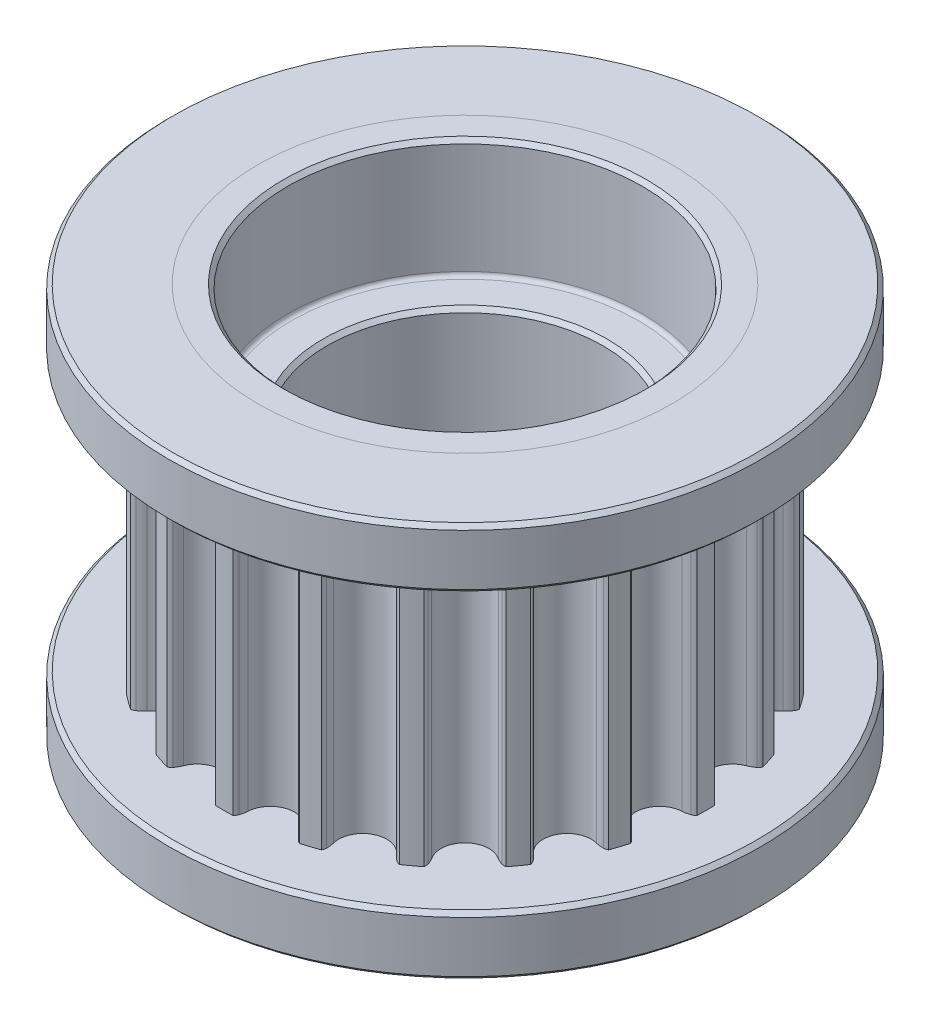
SolidWorks part; units mm, degrees
material "6061-T6 (SS)"
ref_plane "Přední rovina" through (0, 0, 0) normal (0, 0, 1) x (1, 0, 0)
ref_plane "Horní rovina" through (0, 0, 0) normal (0, 1, 0) x (1, 0, 0)
ref_plane "Pravá rovina" through (0, 0, 0) normal (1, 0, 0) x (0, 0, -1)
sketch "Skica1" plane through (0, 0, 0) normal (0, 0, 1) x (1, 0, 0)
  line L0 (4.5, 10) -> (5.25, 10)
  line L1 (5.25, 10) -> (5.25, 8.5)
  line L2 (5.25, 8.5) -> (6.11, 8.5)
  line L3 (6.11, 8.5) -> (6.11, 1.5)
  line L4 (6.11, 1.5) -> (5.25, 1.5)
  line L5 (5.25, 1.5) -> (5.25, 0)
  line L6 (5.25, 0) -> (4.5, 0)
  line L8 (4.5, 10) -> (4.5, 7)
  line L9 (4.5, 7) -> (3.5, 7)
  line L10 (3.5, 7) -> (3.5, 3)
  line L11 (3.5, 3) -> (4.5, 3)
  line L12 (4.5, 3) -> (4.5, 0)
  line L13 (0, 0) -> (0, -4.1646) construction
  dimension "D1" = 10
  dimension "D2" = 7
  dimension "D3" = 4.5
  dimension "D4" = 3.5
  dimension "D5" = 6.11
  dimension "D6" = 3
  dimension "D7" = 5.25
revolve "Rotovat1" add sketch "Skica1" angle 360 about L13
chamfer "Zkosení1" distance 0.1 angle 45 4 edges at (0, 3, 3.5) (0, 0, 4.5) (0, 7, 3.5) (0, 10, 4.5)
fillet "Zaoblit1" radius 0.1 2 edges at (0, 3, 4.5) (0, 7, 4.5)
sketch "Skica11" plane through (0, 8.5, 0) normal (0, 1, 0) x (1, 0, 0)
  line L0 (0, -5.5) -> (0, 5.5) construction
  line L1 (-5.5, 0) -> (5.5, 0) construction
  point P5 (0, 6.1087)
  arc B0 (-3.6824, -4.5256) -> (-4.5256, -3.6824) centre (-4.1938, -4.1938) ccw
  arc B1 (-3.6824, -4.5256) -> (-3.7624, -4.7003) centre (-3.1284, -4.885) ccw
  arc B2 (-3.7624, -4.7003) -> (-3.7672, -4.8088) centre (-3.5429, -4.7643) ccw
  arc B3 (-3.7672, -4.8088) -> (-3.4093, -5.0688) centre (0, 0) ccw
  arc B4 (-3.4093, -5.0688) -> (-3.3076, -5.0308) centre (-3.4362, -4.8418) ccw
  arc B5 (-3.3076, -5.0308) -> (-3.1662, -4.9006) centre (-3.6792, -4.4848) ccw
  arc B6 (-2.1037, -5.442) -> (-3.1662, -4.9006) centre (-2.6926, -5.2845) ccw
  arc B7 (-2.1037, -5.442) -> (-2.1258, -5.6329) centre (-1.4657, -5.6126) ccw
  arc B8 (-2.1258, -5.6329) -> (-2.0968, -5.7376) centre (-1.8973, -5.6259) ccw
  arc B9 (-2.0968, -5.7376) -> (-1.6761, -5.8742) centre (0, 0) ccw
  arc B10 (-1.6761, -5.8742) -> (-1.5911, -5.8066) centre (-1.7719, -5.6667) ccw
  arc B11 (-1.5911, -5.8066) -> (-1.4968, -5.6392) centre (-2.1132, -5.4022) ccw
  arc B12 (-0.319, -5.8257) -> (-1.4968, -5.6392) centre (-0.9278, -5.8579) ccw
  arc B13 (-0.319, -5.8257) -> (-0.2811, -6.0141) centre (0.3404, -5.7909) ccw
  arc B14 (-0.2811, -6.0141) -> (-0.2211, -6.1047) centre (-0.0659, -5.9369) ccw
  arc B15 (-0.2211, -6.1047) -> (0.2211, -6.1047) centre (0, 0) ccw
  arc B16 (0.2211, -6.1047) -> (0.2811, -6.0141) centre (0.0659, -5.9369) ccw
  arc B17 (0.2811, -6.0141) -> (0.319, -5.8257) centre (-0.3404, -5.7909) ccw
  arc B18 (1.4968, -5.6392) -> (0.319, -5.8257) centre (0.9278, -5.8579) ccw
  arc B19 (1.4968, -5.6392) -> (1.5911, -5.8066) centre (2.1132, -5.4022) ccw
  arc B20 (1.5911, -5.8066) -> (1.6761, -5.8742) centre (1.7719, -5.6667) ccw
  arc B21 (1.6761, -5.8742) -> (2.0968, -5.7376) centre (0, 0) ccw
  arc B22 (2.0968, -5.7376) -> (2.1258, -5.6329) centre (1.8973, -5.6259) ccw
  arc B23 (2.1258, -5.6329) -> (2.1037, -5.442) centre (1.4657, -5.6126) ccw
  arc B24 (3.1662, -4.9006) -> (2.1037, -5.442) centre (2.6926, -5.2845) ccw
  arc B25 (3.1662, -4.9006) -> (3.3076, -5.0308) centre (3.6792, -4.4848) ccw
  arc B26 (3.3076, -5.0308) -> (3.4093, -5.0688) centre (3.4362, -4.8418) ccw
  arc B27 (3.4093, -5.0688) -> (3.7672, -4.8088) centre (0, 0) ccw
  arc B28 (3.7672, -4.8088) -> (3.7624, -4.7003) centre (3.5429, -4.7643) ccw
  arc B29 (3.7624, -4.7003) -> (3.6824, -4.5256) centre (3.1284, -4.885) ccw
  arc B30 (4.5256, -3.6824) -> (3.6824, -4.5256) centre (4.1938, -4.1938) ccw
  arc B31 (4.5256, -3.6824) -> (4.7003, -3.7624) centre (4.885, -3.1284) ccw
  arc B32 (4.7003, -3.7624) -> (4.8088, -3.7672) centre (4.7643, -3.5429) ccw
  arc B33 (4.8088, -3.7672) -> (5.0688, -3.4093) centre (0, 0) ccw
  arc B34 (5.0688, -3.4093) -> (5.0308, -3.3076) centre (4.8418, -3.4362) ccw
  arc B35 (5.0308, -3.3076) -> (4.9006, -3.1662) centre (4.4848, -3.6792) ccw
  arc B36 (5.442, -2.1037) -> (4.9006, -3.1662) centre (5.2845, -2.6926) ccw
  arc B37 (5.442, -2.1037) -> (5.6329, -2.1258) centre (5.6126, -1.4657) ccw
  arc B38 (5.6329, -2.1258) -> (5.7376, -2.0968) centre (5.6259, -1.8973) ccw
  arc B39 (5.7376, -2.0968) -> (5.8742, -1.6761) centre (0, 0) ccw
  arc B40 (5.8742, -1.6761) -> (5.8066, -1.5911) centre (5.6667, -1.7719) ccw
  arc B41 (5.8066, -1.5911) -> (5.6392, -1.4968) centre (5.4022, -2.1132) ccw
  arc B42 (5.8257, -0.319) -> (5.6392, -1.4968) centre (5.8579, -0.9278) ccw
  arc B43 (5.8257, -0.319) -> (6.0141, -0.2811) centre (5.7909, 0.3404) ccw
  arc B44 (6.0141, -0.2811) -> (6.1047, -0.2211) centre (5.9369, -0.0659) ccw
  arc B45 (6.1047, -0.2211) -> (6.1047, 0.2211) centre (0, 0) ccw
  arc B46 (6.1047, 0.2211) -> (6.0141, 0.2811) centre (5.9369, 0.0659) ccw
  arc B47 (6.0141, 0.2811) -> (5.8257, 0.319) centre (5.7909, -0.3404) ccw
  arc B48 (5.6392, 1.4968) -> (5.8257, 0.319) centre (5.8579, 0.9278) ccw
  arc B49 (5.6392, 1.4968) -> (5.8066, 1.5911) centre (5.4022, 2.1132) ccw
  arc B50 (5.8066, 1.5911) -> (5.8742, 1.6761) centre (5.6667, 1.7719) ccw
  arc B51 (5.8742, 1.6761) -> (5.7376, 2.0968) centre (0, 0) ccw
  arc B52 (5.7376, 2.0968) -> (5.6329, 2.1258) centre (5.6259, 1.8973) ccw
  arc B53 (5.6329, 2.1258) -> (5.442, 2.1037) centre (5.6126, 1.4657) ccw
  arc B54 (4.9006, 3.1662) -> (5.442, 2.1037) centre (5.2845, 2.6926) ccw
  arc B55 (4.9006, 3.1662) -> (5.0308, 3.3076) centre (4.4848, 3.6792) ccw
  arc B56 (5.0308, 3.3076) -> (5.0688, 3.4093) centre (4.8418, 3.4362) ccw
  arc B57 (5.0688, 3.4093) -> (4.8088, 3.7672) centre (0, 0) ccw
  arc B58 (4.8088, 3.7672) -> (4.7003, 3.7624) centre (4.7643, 3.5429) ccw
  arc B59 (4.7003, 3.7624) -> (4.5256, 3.6824) centre (4.885, 3.1284) ccw
  arc B60 (3.6824, 4.5256) -> (4.5256, 3.6824) centre (4.1938, 4.1938) ccw
  arc B61 (3.6824, 4.5256) -> (3.7624, 4.7003) centre (3.1284, 4.885) ccw
  arc B62 (3.7624, 4.7003) -> (3.7672, 4.8088) centre (3.5429, 4.7643) ccw
  arc B63 (3.7672, 4.8088) -> (3.4093, 5.0688) centre (0, 0) ccw
  arc B64 (3.4093, 5.0688) -> (3.3076, 5.0308) centre (3.4362, 4.8418) ccw
  arc B65 (3.3076, 5.0308) -> (3.1662, 4.9006) centre (3.6792, 4.4848) ccw
  arc B66 (2.1037, 5.442) -> (3.1662, 4.9006) centre (2.6926, 5.2845) ccw
  arc B67 (2.1037, 5.442) -> (2.1258, 5.6329) centre (1.4657, 5.6126) ccw
  arc B68 (2.1258, 5.6329) -> (2.0968, 5.7376) centre (1.8973, 5.6259) ccw
  arc B69 (2.0968, 5.7376) -> (1.6761, 5.8742) centre (0, 0) ccw
  arc B70 (1.6761, 5.8742) -> (1.5911, 5.8066) centre (1.7719, 5.6667) ccw
  arc B71 (1.5911, 5.8066) -> (1.4968, 5.6392) centre (2.1132, 5.4022) ccw
  arc B72 (0.319, 5.8257) -> (1.4968, 5.6392) centre (0.9278, 5.8579) ccw
  arc B73 (0.319, 5.8257) -> (0.2811, 6.0141) centre (-0.3404, 5.7909) ccw
  arc B74 (0.2811, 6.0141) -> (0.2211, 6.1047) centre (0.0659, 5.9369) ccw
  arc B75 (0.2211, 6.1047) -> (-0.2211, 6.1047) centre (0, 0) ccw
  arc B76 (-0.2211, 6.1047) -> (-0.2811, 6.0141) centre (-0.0659, 5.9369) ccw
  arc B77 (-0.2811, 6.0141) -> (-0.319, 5.8257) centre (0.3404, 5.7909) ccw
  arc B78 (-1.4968, 5.6392) -> (-0.319, 5.8257) centre (-0.9278, 5.8579) ccw
  arc B79 (-1.4968, 5.6392) -> (-1.5911, 5.8066) centre (-2.1132, 5.4022) ccw
  arc B80 (-1.5911, 5.8066) -> (-1.6761, 5.8742) centre (-1.7719, 5.6667) ccw
  arc B81 (-1.6761, 5.8742) -> (-2.0968, 5.7376) centre (0, 0) ccw
  arc B82 (-2.0968, 5.7376) -> (-2.1258, 5.6329) centre (-1.8973, 5.6259) ccw
  arc B83 (-2.1258, 5.6329) -> (-2.1037, 5.442) centre (-1.4657, 5.6126) ccw
  arc B84 (-3.1662, 4.9006) -> (-2.1037, 5.442) centre (-2.6926, 5.2845) ccw
  arc B85 (-3.1662, 4.9006) -> (-3.3076, 5.0308) centre (-3.6792, 4.4848) ccw
  arc B86 (-3.3076, 5.0308) -> (-3.4093, 5.0688) centre (-3.4362, 4.8418) ccw
  arc B87 (-3.4093, 5.0688) -> (-3.7672, 4.8088) centre (0, 0) ccw
  arc B88 (-3.7672, 4.8088) -> (-3.7624, 4.7003) centre (-3.5429, 4.7643) ccw
  arc B89 (-3.7624, 4.7003) -> (-3.6824, 4.5256) centre (-3.1284, 4.885) ccw
  arc B90 (-4.5256, 3.6824) -> (-3.6824, 4.5256) centre (-4.1938, 4.1938) ccw
  arc B91 (-4.5256, 3.6824) -> (-4.7003, 3.7624) centre (-4.885, 3.1284) ccw
  arc B92 (-4.7003, 3.7624) -> (-4.8088, 3.7672) centre (-4.7643, 3.5429) ccw
  arc B93 (-4.8088, 3.7672) -> (-5.0688, 3.4093) centre (0, 0) ccw
  arc B94 (-5.0688, 3.4093) -> (-5.0308, 3.3076) centre (-4.8418, 3.4362) ccw
  arc B95 (-5.0308, 3.3076) -> (-4.9006, 3.1662) centre (-4.4848, 3.6792) ccw
  arc B96 (-5.442, 2.1037) -> (-4.9006, 3.1662) centre (-5.2845, 2.6926) ccw
  arc B97 (-5.442, 2.1037) -> (-5.6329, 2.1258) centre (-5.6126, 1.4657) ccw
  arc B98 (-5.6329, 2.1258) -> (-5.7376, 2.0968) centre (-5.6259, 1.8973) ccw
  arc B99 (-5.7376, 2.0968) -> (-5.8742, 1.6761) centre (0, 0) ccw
  arc B100 (-5.8742, 1.6761) -> (-5.8066, 1.5911) centre (-5.6667, 1.7719) ccw
  arc B101 (-5.8066, 1.5911) -> (-5.6392, 1.4968) centre (-5.4022, 2.1132) ccw
  arc B102 (-5.8257, 0.319) -> (-5.6392, 1.4968) centre (-5.8579, 0.9278) ccw
  arc B103 (-5.8257, 0.319) -> (-6.0141, 0.2811) centre (-5.7909, -0.3404) ccw
  arc B104 (-6.0141, 0.2811) -> (-6.1047, 0.2211) centre (-5.9369, 0.0659) ccw
  arc B105 (-6.1047, 0.2211) -> (-6.1047, -0.2211) centre (0, 0) ccw
  arc B106 (-6.1047, -0.2211) -> (-6.0141, -0.2811) centre (-5.9369, -0.0659) ccw
  arc B107 (-6.0141, -0.2811) -> (-5.8257, -0.319) centre (-5.7909, 0.3404) ccw
  arc B108 (-5.6392, -1.4968) -> (-5.8257, -0.319) centre (-5.8579, -0.9278) ccw
  arc B109 (-5.6392, -1.4968) -> (-5.8066, -1.5911) centre (-5.4022, -2.1132) ccw
  arc B110 (-5.8066, -1.5911) -> (-5.8742, -1.6761) centre (-5.6667, -1.7719) ccw
  arc B111 (-5.8742, -1.6761) -> (-5.7376, -2.0968) centre (0, 0) ccw
  arc B112 (-5.7376, -2.0968) -> (-5.6329, -2.1258) centre (-5.6259, -1.8973) ccw
  arc B113 (-5.6329, -2.1258) -> (-5.442, -2.1037) centre (-5.6126, -1.4657) ccw
  arc B114 (-4.9006, -3.1662) -> (-5.442, -2.1037) centre (-5.2845, -2.6926) ccw
  arc B115 (-4.9006, -3.1662) -> (-5.0308, -3.3076) centre (-4.4848, -3.6792) ccw
  arc B116 (-5.0308, -3.3076) -> (-5.0688, -3.4093) centre (-4.8418, -3.4362) ccw
  arc B117 (-5.0688, -3.4093) -> (-4.8088, -3.7672) centre (0, 0) ccw
  arc B118 (-4.8088, -3.7672) -> (-4.7003, -3.7624) centre (-4.7643, -3.5429) ccw
  arc B119 (-4.7003, -3.7624) -> (-4.5256, -3.6824) centre (-4.885, -3.1284) ccw
sketch_block_instance "Blok1-1"
sketch_block "Blok1"
extrude "Odebrat vysunutím1" cut sketch "Skica11" against normal through all flip side to cut
sketch "Skica10" plane through (0, 10, 0) normal (0, 1, 0) x (1, 0, 0)
  circle A0 centre (0, 0) radius 7.5
  circle A1 centre (0, 0) radius 5.25 construction
  circle A2 centre (0, 0) radius 5.25
  dimension "D1" = 15
extrude "Přidat vysunutím1" add sketch "Skica10" against normal up to surface (1.5 mm away) separate body up to face at (0, 8.5, 5.25)
sketch "Skica12" plane through (0, 0, 0) normal (0, -1, 0) x (1, 0, 0)
  circle A0 centre (0, 0) radius 7.5
  circle A1 centre (0, 0) radius 5.25 construction
  circle A2 centre (0, 0) radius 5.25
  circle A3 centre (0, 0) radius 7.5 construction
extrude "Přidat vysunutím2" add sketch "Skica12" against normal up to surface (1.5 mm away) separate body up to face at (0, 1.5, 5.25)
chamfer "Zkosení2" distance 0.1 angle 45 2 edges at (0, 8.5, -7.5) (0, 10, 7.5)
chamfer "Zkosení3" distance 0.1 angle 45 2 edges at (0, 0, -7.5) (0, 1.5, 7.5)
